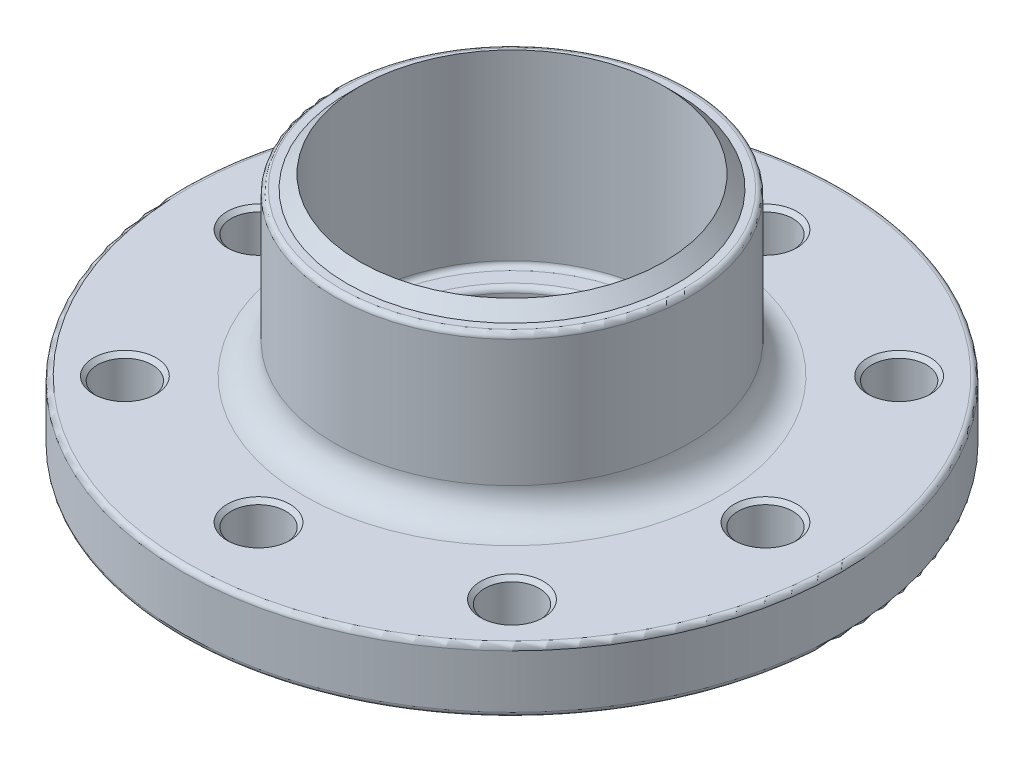
SolidWorks part; units mm, degrees
ref_plane "Plano frontal" through (0, 0, 0) normal (0, 0, 1) x (1, 0, 0)
ref_plane "Plano superior" through (0, 0, 0) normal (0, 1, 0) x (1, 0, 0)
ref_plane "Plano direito" through (0, 0, 0) normal (1, 0, 0) x (0, 0, -1)
sketch "Esboço1" plane through (0, 0, 0) normal (0, 0, 1) x (1, 0, 0)
  line L0 (0, -46.9816) -> (0, 59.8925) construction
  line L1 (30, 49.1832) -> (32.5, 46.6832)
  line L2 (32.5, 46.6832) -> (35, 46.6832)
  line L3 (35, 46.6832) -> (35, 14.6832)
  line L4 (35, 14.6832) -> (65, 14.6832)
  line L5 (65, 14.6832) -> (65, 2.1832)
  line L6 (65, 2.1832) -> (27.5, 2.1832)
  line L7 (27.5, 2.1832) -> (27.5, -15.8168)
  line L8 (27.5, -15.8168) -> (25, -15.8168)
  line L9 (25, -15.8168) -> (25, 12.1832)
  line L10 (25, 12.1832) -> (30, 12.1832)
  line L11 (30, 12.1832) -> (30, 49.1832)
  dimension "D1" = 37
  dimension "D2" = 2.5
  dimension "D3" = 30
  dimension "D4" = 25
  dimension "D5" = 27.5
  dimension "D6" = 65
  dimension "D7" = 35
  dimension "D8" = 45
  dimension "D9" = 18
  dimension "D10" = 12.5
  dimension "D11" = 65
revolve "Revolução1" add sketch "Esboço1" angle 360 about L0
fillet "Filete1" radius 6 1 edges at (0, 14.6832, -35)
fillet "Filete2" radius 1 4 edges at (0, 12.1832, -30) (0, 2.1832, -65) (0, 14.6832, -65) (0, 46.6832, -35)
fillet "Filete3" radius 1 4 edges at (0, 12.1832, -25) (0, -15.8168, -25) (0, -15.8168, -27.5) (0, 2.1832, -27.5)
sketch "Esboço2" plane through (0, 2.1832, 0) normal (0, -1, 0) x (-1, 0, 0)
  circle A0 centre (0, 0) radius 50 construction
  circle A1 centre (0, -50) radius 5.4
  circle A2 centre (-50, 0) radius 5.4
  circle A3 centre (0, 50) radius 5.4
  circle A4 centre (50, 0) radius 5.4
  point P14 (0, 0)
  dimension "D1" = 100
  dimension "D2" = 10.8
  dimension "D3" = 4
extrude "Corte-extrusão1" cut sketch "Esboço2" against normal through all
sketch "Esboço3" plane through (0, 2.1832, 0) normal (0, -1, 0) x (-1, 0, 0)
  circle A0 centre (0, 0) radius 54 construction
  circle A2 centre (38.1838, -38.1838) radius 5.4
  circle A4 centre (-38.1838, -38.1838) radius 5.4
  circle A6 centre (-38.1838, 38.1838) radius 5.4
  circle A8 centre (38.1838, 38.1838) radius 5.4
  point P21 (0, 0)
extrude "Corte-extrusão2" cut sketch "Esboço3" against normal through all
chamfer "Chanfro1" distance 0.8 angle 45 16 edges at (-38.1838, 2.1832, -43.5838) (-38.1838, 14.6832, -32.7838) (0, 2.1832, -55.4) (0, 14.6832, -44.6) (38.1838, 2.1832, -43.5838) (38.1838, 14.6832, -32.7838) (50, 2.1832, -5.4) (50, 14.6832, 5.4) (38.1838, 2.1832, 32.7838) (38.1838, 14.6832, 43.5838) (0, 2.1832, 44.6) (0, 14.6832, 55.4) (-38.1838, 2.1832, 32.7838) (-38.1838, 14.6832, 43.5838) (-50, 2.1832, -5.4) (-50, 14.6832, 5.4)
